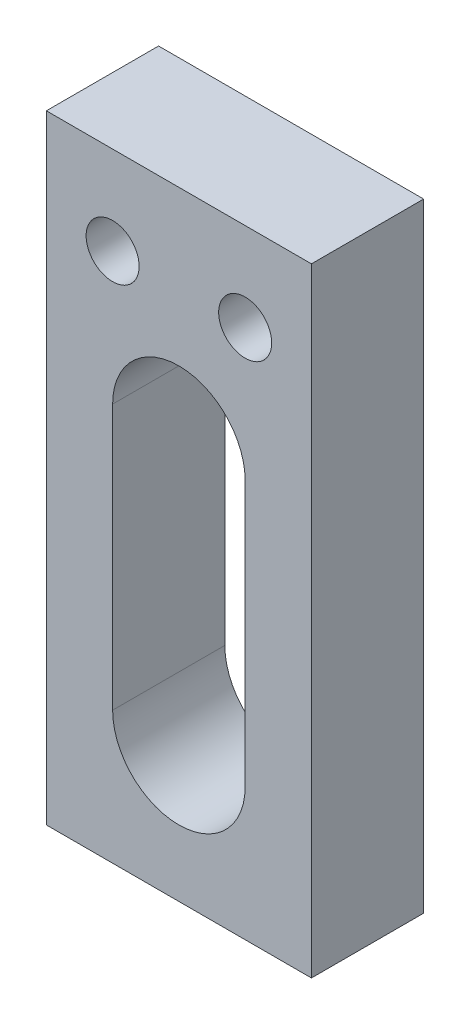
SolidWorks part; units mm, degrees
ref_plane "Alzado" through (0, 0, 0) normal (0, 0, 1) x (1, 0, 0)
ref_plane "Planta" through (0, 0, 0) normal (0, 1, 0) x (1, 0, 0)
ref_plane "Vista lateral" through (0, 0, 0) normal (1, 0, 0) x (0, 0, -1)
sketch "Croquis1" plane through (0, 0, 0) normal (0, 0, 1) x (1, 0, 0)
  line L0 (0, 10) -> (0, -20) construction
  line L1 (-15, 35) -> (15, 35)
  line L2 (-15, 35) -> (-15, -35)
  line L3 (-15, -35) -> (15, -35)
  line L4 (15, 35) -> (15, -35)
  line L5 (-15, 35) -> (15, -35) construction
  line L6 (-15, -35) -> (15, 35) construction
  line L7 (7.5, 10) -> (7.5, -20)
  line L8 (-7.5, 10) -> (-7.5, -20)
  arc A0 (7.5, 10) -> (-7.5, 10) centre (0, 10) ccw
  arc A1 (-7.5, -20) -> (7.5, -20) centre (0, -20) ccw
  circle A2 centre (-7.5, 25) radius 3
  circle A3 centre (7.5, 25) radius 3
  point P0 (0, 0)
  point P8 (0, -5)
  dimension "D3" = 7.5
  dimension "D6" = 6
  dimension "D7" = 6
  dimension "D1" = 70
  dimension "D2" = 30
  dimension "D4" = 5
  dimension "D5" = 30
  dimension "D8" = 15
  dimension "D9" = 7.5
  dimension "D10" = 10
extrude "Saliente-Extruir1" add sketch "Croquis1" along normal blind 12.7
